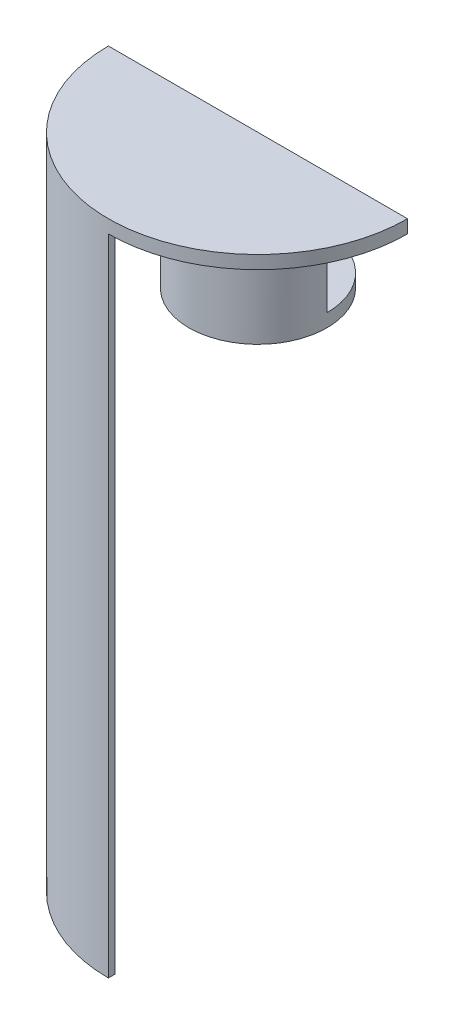
SolidWorks part; units mm, degrees
ref_plane "Alzado" through (0, 0, 0) normal (0, 0, 1) x (1, 0, 0)
ref_plane "Planta" through (0, 0, 0) normal (0, 1, 0) x (1, 0, 0)
ref_plane "Vista lateral" through (0, 0, 0) normal (1, 0, 0) x (0, 0, -1)
sketch "Croquis1" plane through (0, 0, 0) normal (0, 1, 0) x (1, 0, 0)
  circle A0 centre (0, 0) radius 30
  circle A1 centre (0, 0) radius 43.5
  dimension "D1" = 60
  dimension "D2" = 87
extrude "Saliente-Extruir1" add sketch "Croquis1" along normal blind 4
sketch "Croquis2" plane through (0, 0, 0) normal (0, 1, 0) x (1, 0, 0)
  circle A0 centre (0, 0) radius 20
  circle A1 centre (0, 0) radius 30
  dimension "D1" = 40
  dimension "D2" = 60
extrude "Saliente-Extruir2" add sketch "Croquis2" along normal blind 4
sketch "Croquis3" plane through (0, 0, 0) normal (0, 1, 0) x (1, 0, 0)
  circle A0 centre (0, 0) radius 20
  circle A1 centre (0, 0) radius 30
  dimension "D1" = 40
  dimension "D2" = 60
extrude "Cortar-Extruir1" cut sketch "Croquis3" along normal blind 2
sketch "Croquis5" plane through (0, 0, 0) normal (0, 1, 0) x (1, 0, 0)
  circle A0 centre (0, 0) radius 37.5
  circle A1 centre (0, -37.5) radius 3
  circle A2 centre (-37.5, 0) radius 3
  circle A3 centre (0, 37.5) radius 3
  circle A4 centre (37.5, 0) radius 3
  point P14 (0, 0)
  dimension "D1" = 75
  dimension "D2" = 6
  dimension "D3" = 4
extrude "Cortar-Extruir3" cut sketch "Croquis5" along normal up to surface (4 mm away) contours A0 A1 | A0 A1 | A0 A4 | A0 A4 | A0 A3 | A0 A3 | A0 A2 | A0 A2
sketch "Croquis7" plane through (0, 0, 0) normal (0, 1, 0) x (1, 0, 0)
  line L0 (-45.5, 0) -> (-43.5, 0)
  line L1 (43.5, 0) -> (45.5, 0)
  arc A0 (-43.5, 0) -> (43.5, 0) centre (0, 0) ccw
  arc A1 (-45.5, 0) -> (45.5, 0) centre (0, 0) ccw
  dimension "D1" = 87
  dimension "D2" = 91
extrude "Saliente-Extruir3" add sketch "Croquis7" along normal blind 200
sketch "Croquis8" plane through (0, 200, 0) normal (0, 1, 0) x (1, 0, 0)
  circle A0 centre (0, 0) radius 45.5
extrude "Saliente-Extruir4" add sketch "Croquis8" along normal blind 4
sketch "Croquis9" plane through (0, 200, 0) normal (0, -1, 0) x (1, 0, 0)
  circle A0 centre (0, 0) radius 19
  circle A1 centre (0, 0) radius 21
  dimension "D1" = 38
  dimension "D2" = 42
extrude "Saliente-Extruir5" add sketch "Croquis9" along normal blind 33
sketch "Croquis10" plane through (0, 167, 0) normal (0, -1, 0) x (1, 0, 0)
  line L0 (21, 0) -> (-21, 0)
  arc A0 (-21, 0) -> (21, 0) centre (0, 0) ccw
extrude "Cortar-Extruir6" cut sketch "Croquis10" against normal blind 33
sketch "Croquis11" plane through (0, 167, 0) normal (0, -1, 0) x (1, 0, 0)
  circle A0 centre (0, 0) radius 21
extrude "Saliente-Extruir6" add sketch "Croquis11" along normal blind 4
sketch "Croquis12" plane through (0, 163, 0) normal (0, -1, 0) x (1, 0, 0)
  line L0 (-3, 0) -> (-3, -20.7846)
  line L1 (3, 0) -> (3, -20.7846)
  arc A0 (3, 0) -> (-3, 0) centre (0, 0) ccw
  circle A1 centre (0, 0) radius 21 construction
  arc A2 (-3, -20.7846) -> (3, -20.7846) centre (0, 0) ccw
  dimension "D1" = 6
extrude "Cortar-Extruir7" cut sketch "Croquis12" against normal blind 4
sketch "Croquis14" plane through (0, 0, 0) normal (0, -1, 0) x (1, 0, 0)
  circle A0 centre (0, 0) radius 45.5
extrude "Cortar-Extruir9" cut sketch "Croquis14" against normal blind 4
sketch "Croquis15" plane through (0, 0, 0) normal (0, 1, 0) x (1, 0, 0)
  line L0 (43.5, 0) -> (45.5, 0)
  line L1 (0, -43.5) -> (0, -45.5)
  arc A0 (0, -45.5) -> (45.5, 0) centre (0, 0) ccw
  arc A1 (0, -43.5) -> (43.5, 0) centre (0, 0) ccw
extrude "Cortar-Extruir11" cut sketch "Croquis15" along normal up to surface (200 mm away) up to face at (0, 200, 10)
sketch "Croquis16" plane through (0, 163, 0) normal (0, -1, 0) x (1, 0, 0)
  circle A0 centre (0, 0) radius 10
  dimension "D1" = 20
extrude "Cortar-Extruir12" cut sketch "Croquis16" against normal blind 4
sketch "Croquis17" plane through (0, 0, 0) normal (0, 1, 0) x (1, 0, 0)
  line L1 (-45.5, 0) -> (45.5, 0)
  arc A2 (45.5, 0) -> (-45.5, 0) centre (0, 0) ccw
extrude "Cortar-Extruir13" cut sketch "Croquis17" along normal up to surface (4 mm away) from surface at 200 up to face at (0, 204, 45.5) starting at face at (-10.7714, 200, 10.7714)
